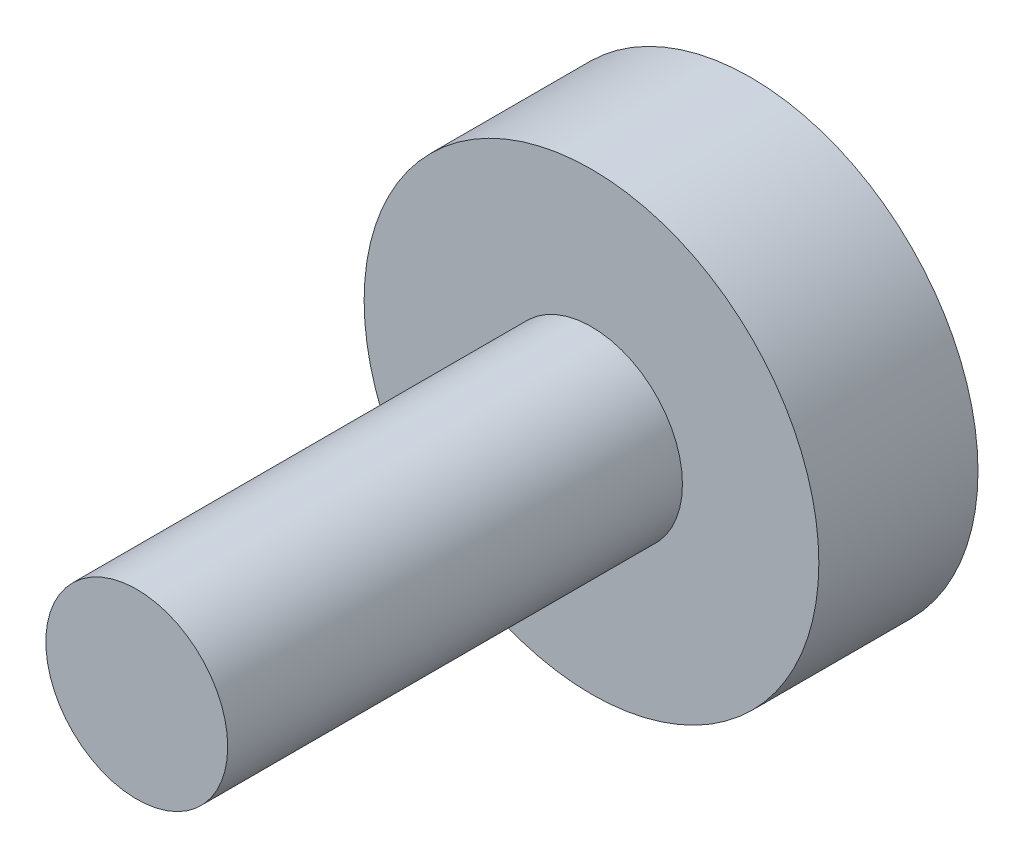
SolidWorks part; units mm, degrees
ref_plane "Front Plane" through (0, 0, 0) normal (0, 0, 1) x (1, 0, 0)
ref_plane "Top Plane" through (0, 0, 0) normal (0, 1, 0) x (1, 0, 0)
ref_plane "Right Plane" through (0, 0, 0) normal (1, 0, 0) x (0, 0, -1)
sketch "Sketch1" plane through (0, 0, 0) normal (0, 0, 1) x (1, 0, 0)
  circle A1 centre (0, 0) radius 10
  dimension "D1" = 20
extrude "Boss-Extrude1" add sketch "Sketch1" along normal blind 7
sketch "Sketch3" plane through (0, 0, 7) normal (0, 0, 1) x (1, 0, 0)
  circle A0 centre (0, 0) radius 4
  dimension "D1" = 8
extrude "Boss-Extrude2" add sketch "Sketch3" along normal blind 20
